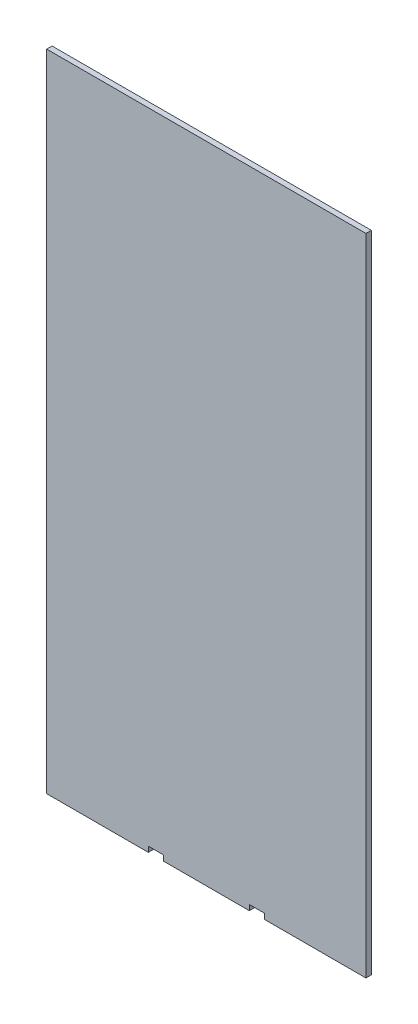
SolidWorks part; units mm, degrees
ref_plane "Front Plane" through (0, 0, 0) normal (0, 0, 1) x (1, 0, 0)
ref_plane "Top Plane" through (0, 0, 0) normal (0, 1, 0) x (1, 0, 0)
ref_plane "Right Plane" through (0, 0, 0) normal (1, 0, 0) x (0, 0, -1)
sketch "Sketch1" plane through (0, 0, 0) normal (0, 0, 1) x (1, 0, 0)
  line L0 (148.5, -7) -> (-148.5, -7) construction
  line L1 (-148.5, -607) -> (148.5, -607)
  line L2 (-148.5, -607) -> (-148.5, -7)
  line L3 (-148.5, -7) -> (148.5, -7)
  line L4 (148.5, -607) -> (148.5, -7)
  line L5 (-148.5, -607) -> (148.5, -7) construction
  line L6 (-148.5, -7) -> (148.5, -607) construction
  line L7 (0, -307) -> (0, 0) construction
  point P0 (0, -307)
  dimension "D2" = 600
extrude "Extrude1" add sketch "Sketch1" against normal blind 5
sketch "Sketch2" plane through (0, 0, -5) normal (0, 0, -1) x (-1, 0, 0)
  line L0 (148.5, -607) -> (-148.5, -607) construction
  line L1 (-54, -607) -> (-40, -607)
  line L2 (-54, -607) -> (-54, -602)
  line L3 (-54, -602) -> (-40, -602)
  line L4 (-40, -607) -> (-40, -602)
  line L5 (0, -607) -> (0, 0) construction
  line L6 (40, -607) -> (54, -607)
  line L7 (40, -607) -> (40, -602)
  line L8 (40, -602) -> (54, -602)
  line L9 (54, -607) -> (54, -602)
  dimension "D1" = 80
  dimension "D2" = 14
  dimension "D3" = 5
extrude "Cut-Extrude1" cut sketch "Sketch2" against normal up to next
